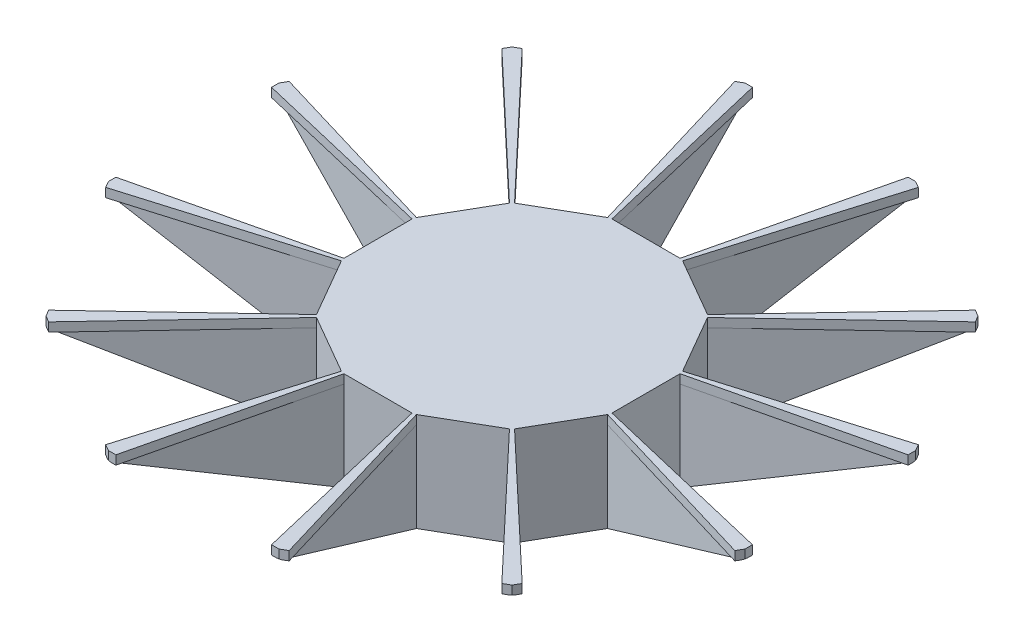
SolidWorks part; units mm, degrees
ref_plane "Front Plane" through (0, 0, 0) normal (0, 0, 1) x (1, 0, 0)
ref_plane "Top Plane" through (0, 0, 0) normal (0, 1, 0) x (1, 0, 0)
ref_plane "Right Plane" through (0, 0, 0) normal (1, 0, 0) x (0, 0, -1)
sketch "Sketch1" plane through (0, 0, 0) normal (0, 1, 0) x (1, 0, 0)
  line L0 (-54.641, -54.641) -> (-20, -74.641) construction
  line L1 (54.641, 54.641) -> (20, 74.641) construction
  line L2 (20, 74.641) -> (-20, 74.641) construction
  line L3 (-20, 74.641) -> (-54.641, 54.641) construction
  line L4 (-54.641, 54.641) -> (-74.641, 20) construction
  line L5 (-74.641, 20) -> (-74.641, -20) construction
  line L6 (-74.641, -20) -> (-54.641, -54.641) construction
  line L7 (-20, -74.641) -> (20, -74.641) construction
  line L8 (20, -74.641) -> (54.641, -54.641) construction
  line L9 (54.641, -54.641) -> (74.641, -20) construction
  line L10 (74.641, -20) -> (74.641, 20) construction
  line L11 (74.641, 20) -> (54.641, 54.641) construction
  line L12 (-51.0863, 175.2019) -> (-20.8966, 74.1234)
  line L25 (47.5, 177.2724) -> (-47.5, 177.2724) construction
  line L26 (-47.5, 177.2724) -> (-129.7724, 129.7724) construction
  line L27 (-129.7724, 129.7724) -> (-177.2724, 47.5) construction
  line L28 (-177.2724, 47.5) -> (-177.2724, -47.5) construction
  line L29 (-177.2724, -47.5) -> (-129.7724, -129.7724) construction
  line L30 (-129.7724, -129.7724) -> (-47.5, -177.2724) construction
  line L31 (-47.5, -177.2724) -> (47.5, -177.2724) construction
  line L32 (47.5, -177.2724) -> (129.7724, -129.7724) construction
  line L33 (129.7724, -129.7724) -> (177.2724, -47.5) construction
  line L34 (177.2724, -47.5) -> (177.2724, 47.5) construction
  line L35 (177.2724, 47.5) -> (129.7724, 129.7724) construction
  line L36 (129.7724, 129.7724) -> (47.5, 177.2724) construction
  line L37 (-43.3589, 177.2724) -> (-18.9647, 74.641)
  line L38 (0, 0) -> (-47.5, 177.2724) construction
  line L39 (51.0863, 175.2019) -> (20.8966, 74.1234)
  line L40 (43.3589, 177.2724) -> (18.9647, 74.641)
  line L41 (131.843, 126.1861) -> (55.1587, 53.7444)
  line L42 (126.1861, 131.843) -> (53.7444, 55.1587)
  line L43 (177.2724, 43.3589) -> (74.641, 18.9647)
  line L44 (175.2019, 51.0863) -> (74.1234, 20.8966)
  line L45 (175.2019, -51.0863) -> (74.1234, -20.8966)
  line L46 (177.2724, -43.3589) -> (74.641, -18.9647)
  line L47 (126.1861, -131.843) -> (53.7444, -55.1587)
  line L48 (131.843, -126.1861) -> (55.1587, -53.7444)
  line L49 (43.3589, -177.2724) -> (18.9647, -74.641)
  line L50 (51.0863, -175.2019) -> (20.8966, -74.1234)
  line L51 (-51.0863, -175.2019) -> (-20.8966, -74.1234)
  line L52 (-43.3589, -177.2724) -> (-18.9647, -74.641)
  line L53 (-131.843, -126.1861) -> (-55.1587, -53.7444)
  line L54 (-126.1861, -131.843) -> (-53.7444, -55.1587)
  line L55 (-177.2724, -43.3589) -> (-74.641, -18.9647)
  line L56 (-175.2019, -51.0863) -> (-74.1234, -20.8966)
  line L57 (-175.2019, 51.0863) -> (-74.1234, 20.8966)
  line L58 (-177.2724, 43.3589) -> (-74.641, 18.9647)
  line L59 (-126.1861, 131.843) -> (-53.7444, 55.1587)
  line L60 (-131.843, 126.1861) -> (-55.1587, 53.7444)
  line L61 (-51.0863, 175.2019) -> (-47.5, 177.2724)
  line L62 (-47.5, 177.2724) -> (-43.3589, 177.2724)
  line L63 (43.3589, 177.2724) -> (47.5, 177.2724)
  line L64 (47.5, 177.2724) -> (51.0863, 175.2019)
  line L65 (126.1861, 131.843) -> (129.7724, 129.7724)
  line L66 (129.7724, 129.7724) -> (131.843, 126.1861)
  line L67 (175.2019, 51.0863) -> (177.2724, 47.5)
  line L68 (177.2724, 47.5) -> (177.2724, 43.3589)
  line L69 (177.2724, -43.3589) -> (177.2724, -47.5)
  line L70 (177.2724, -47.5) -> (175.2019, -51.0863)
  line L71 (131.843, -126.1861) -> (129.7724, -129.7724)
  line L72 (129.7724, -129.7724) -> (126.1861, -131.843)
  line L73 (51.0863, -175.2019) -> (47.5, -177.2724)
  line L74 (47.5, -177.2724) -> (43.3589, -177.2724)
  line L75 (-43.3589, -177.2724) -> (-47.5, -177.2724)
  line L76 (-47.5, -177.2724) -> (-51.0863, -175.2019)
  line L77 (-126.1861, -131.843) -> (-129.7724, -129.7724)
  line L78 (-129.7724, -129.7724) -> (-131.843, -126.1861)
  line L79 (-175.2019, -51.0863) -> (-177.2724, -47.5)
  line L80 (-177.2724, -47.5) -> (-177.2724, -43.3589)
  line L81 (-177.2724, 43.3589) -> (-177.2724, 47.5)
  line L82 (-177.2724, 47.5) -> (-175.2019, 51.0863)
  line L83 (-131.843, 126.1861) -> (-129.7724, 129.7724)
  line L84 (-129.7724, 129.7724) -> (-126.1861, 131.843)
  line L85 (-74.1234, 20.8966) -> (-55.1587, 53.7444)
  line L86 (-53.7444, 55.1587) -> (-20.8966, 74.1234)
  line L87 (-18.9647, 74.641) -> (18.9647, 74.641)
  line L88 (20.8966, 74.1234) -> (53.7444, 55.1587)
  line L89 (55.1587, 53.7444) -> (74.1234, 20.8966)
  line L90 (74.641, 18.9647) -> (74.641, -18.9647)
  line L91 (74.1234, -20.8966) -> (55.1587, -53.7444)
  line L92 (53.7444, -55.1587) -> (20.8966, -74.1234)
  line L93 (18.9647, -74.641) -> (-18.9647, -74.641)
  line L94 (-20.8966, -74.1234) -> (-53.7444, -55.1587)
  line L95 (-55.1587, -53.7444) -> (-74.1234, -20.8966)
  line L96 (-74.641, -18.9647) -> (-74.641, 18.9647)
  circle A0 centre (0, 0) radius 74.641 construction
  circle A1 centre (0, 0) radius 177.2724 construction
  point P1 (0, 177.2724)
  point P36 (0, 74.641)
  dimension "D1" = 40
  dimension "D2" = 95
  dimension "D3" = 8
  dimension "D4" = 2
  dimension "D5" = 12
  dimension "D6" = 12
  dimension "D7" = 12
extrude "Boss-Extrude1" add sketch "Sketch1" along normal blind 5
sketch "Sketch2" plane through (0, 0, 0) normal (0, -1, 0) x (1, 0, 0)
  line L0 (-20.8966, 74.1234) -> (-48.3966, 176.7548)
  line L1 (-20, 74.641) -> (-54.641, 54.641) construction
  line L2 (-54.641, 54.641) -> (-74.641, 20) construction
  line L3 (-74.641, 20) -> (-74.641, -20) construction
  line L4 (-74.641, -20) -> (-54.641, -54.641) construction
  line L5 (-54.641, -54.641) -> (-20, -74.641) construction
  line L6 (-20, -74.641) -> (20, -74.641) construction
  line L7 (20, -74.641) -> (54.641, -54.641) construction
  line L8 (54.641, -54.641) -> (74.641, -20) construction
  line L9 (74.641, -20) -> (74.641, 20) construction
  line L10 (74.641, 20) -> (54.641, 54.641) construction
  line L11 (54.641, 54.641) -> (20, 74.641) construction
  line L12 (20, 74.641) -> (-20, 74.641) construction
  line L13 (-51.0863, 175.2019) -> (-47.5, 177.2724) construction
  line L14 (-18.9647, 74.641) -> (-46.4647, 177.2724)
  line L16 (-47.5, 177.2724) -> (-43.3589, 177.2724) construction
  line L17 (-47.5, 177.2724) -> (-20, 74.641) construction
  line L18 (-48.3966, 176.7548) -> (-47.5, 177.2724)
  line L19 (-47.5, 177.2724) -> (-46.4647, 177.2724)
  line L20 (-20.8966, 74.1234) -> (-53.7444, 55.1587)
  line L21 (18.9647, 74.641) -> (46.4647, 177.2724)
  line L22 (-19.3301, 72.141) -> (-52.8109, 52.8109)
  line L23 (-52.8109, 52.8109) -> (-72.141, 19.3301)
  line L24 (-72.141, 19.3301) -> (-72.141, -19.3301)
  line L25 (-72.141, -19.3301) -> (-52.8109, -52.8109)
  line L26 (-52.8109, -52.8109) -> (-19.3301, -72.141)
  line L27 (-19.3301, -72.141) -> (19.3301, -72.141)
  line L28 (19.3301, -72.141) -> (52.8109, -52.8109)
  line L29 (52.8109, -52.8109) -> (72.141, -19.3301)
  line L30 (72.141, -19.3301) -> (72.141, 19.3301)
  line L31 (72.141, 19.3301) -> (52.8109, 52.8109)
  line L32 (52.8109, 52.8109) -> (19.3301, 72.141)
  line L33 (19.3301, 72.141) -> (-19.3301, 72.141)
  line L34 (20.8966, 74.1234) -> (48.3966, 176.7548)
  line L35 (18.9647, 74.641) -> (-18.9647, 74.641)
  line L36 (46.4647, 177.2724) -> (47.5, 177.2724)
  line L37 (47.5, 177.2724) -> (48.3966, 176.7548)
  line L38 (53.7444, 55.1587) -> (128.8758, 130.2901)
  line L39 (55.1587, 53.7444) -> (130.2901, 128.8758)
  line L40 (53.7444, 55.1587) -> (20.8966, 74.1234)
  line L41 (128.8758, 130.2901) -> (129.7724, 129.7724)
  line L42 (129.7724, 129.7724) -> (130.2901, 128.8758)
  line L43 (74.1234, 20.8966) -> (176.7548, 48.3966)
  line L44 (74.641, 18.9647) -> (177.2724, 46.4647)
  line L45 (74.1234, 20.8966) -> (55.1587, 53.7444)
  line L46 (176.7548, 48.3966) -> (177.2724, 47.5)
  line L47 (177.2724, 47.5) -> (177.2724, 46.4647)
  line L48 (74.641, -18.9647) -> (177.2724, -46.4647)
  line L49 (74.1234, -20.8966) -> (176.7548, -48.3966)
  line L50 (74.641, -18.9647) -> (74.641, 18.9647)
  line L51 (177.2724, -46.4647) -> (177.2724, -47.5)
  line L52 (177.2724, -47.5) -> (176.7548, -48.3966)
  line L53 (55.1587, -53.7444) -> (130.2901, -128.8758)
  line L54 (53.7444, -55.1587) -> (128.8758, -130.2901)
  line L55 (55.1587, -53.7444) -> (74.1234, -20.8966)
  line L56 (130.2901, -128.8758) -> (129.7724, -129.7724)
  line L57 (129.7724, -129.7724) -> (128.8758, -130.2901)
  line L58 (20.8966, -74.1234) -> (48.3966, -176.7548)
  line L59 (18.9647, -74.641) -> (46.4647, -177.2724)
  line L60 (20.8966, -74.1234) -> (53.7444, -55.1587)
  line L61 (48.3966, -176.7548) -> (47.5, -177.2724)
  line L62 (47.5, -177.2724) -> (46.4647, -177.2724)
  line L63 (-18.9647, -74.641) -> (-46.4647, -177.2724)
  line L64 (-20.8966, -74.1234) -> (-48.3966, -176.7548)
  line L65 (-18.9647, -74.641) -> (18.9647, -74.641)
  line L66 (-46.4647, -177.2724) -> (-47.5, -177.2724)
  line L67 (-47.5, -177.2724) -> (-48.3966, -176.7548)
  line L68 (-53.7444, -55.1587) -> (-128.8758, -130.2901)
  line L69 (-55.1587, -53.7444) -> (-130.2901, -128.8758)
  line L70 (-53.7444, -55.1587) -> (-20.8966, -74.1234)
  line L71 (-128.8758, -130.2901) -> (-129.7724, -129.7724)
  line L72 (-129.7724, -129.7724) -> (-130.2901, -128.8758)
  line L73 (-74.1234, -20.8966) -> (-176.7548, -48.3966)
  line L74 (-74.641, -18.9647) -> (-177.2724, -46.4647)
  line L75 (-74.1234, -20.8966) -> (-55.1587, -53.7444)
  line L76 (-176.7548, -48.3966) -> (-177.2724, -47.5)
  line L77 (-177.2724, -47.5) -> (-177.2724, -46.4647)
  line L78 (-74.641, 18.9647) -> (-177.2724, 46.4647)
  line L79 (-74.1234, 20.8966) -> (-176.7548, 48.3966)
  line L80 (-74.641, 18.9647) -> (-74.641, -18.9647)
  line L81 (-177.2724, 46.4647) -> (-177.2724, 47.5)
  line L82 (-177.2724, 47.5) -> (-176.7548, 48.3966)
  line L83 (-55.1587, 53.7444) -> (-130.2901, 128.8758)
  line L84 (-53.7444, 55.1587) -> (-128.8758, 130.2901)
  line L85 (-55.1587, 53.7444) -> (-74.1234, 20.8966)
  line L86 (-130.2901, 128.8758) -> (-129.7724, 129.7724)
  line L87 (-129.7724, 129.7724) -> (-128.8758, 130.2901)
  line L88 (-129.7724, 129.7724) -> (-126.1861, 131.843) construction
  line L89 (-131.843, 126.1861) -> (-129.7724, 129.7724) construction
  circle A0 centre (0, 0) radius 74.641 construction
  circle A1 centre (0, 0) radius 72.141 construction
  point P2 (0, 72.141)
  dimension "D1" = 40
  dimension "D2" = 5
  dimension "D3" = 12
extrude "Boss-Extrude2" add sketch "Sketch2" along normal blind 50
sketch "Sketch4" plane through (0.7071, 0, 0.7071) normal (0.7071, 0, 0.7071) x (0.7071, 0, -0.7071)
  line L0 (-185.0061, 0.8808) -> (-77.0061, -50)
  line L4 (-185.0061, 0.8808) -> (-185.0061, -50)
  line L5 (-185.0061, -50) -> (-77.0061, -50)
  line M4 (-77.0061, 0) -> (-183.258, 0)
  line M5 (-183.258, 0) -> (-183.258, -50)
  line M6 (-183.258, -50) -> (-77.0061, -50)
  dimension "D1" = 108
  dimension "D2" = 25.226
extrude "Cut-Extrude2" cut sketch "Sketch4" against normal up to next contours L0 M4 M5 M6 | L4 L5 L0 M5 M4
pattern_circular "CirPattern1" count 12 over 360 about axis through (0, 0, 0) along (0, 1, 0) of "Cut-Extrude2"
